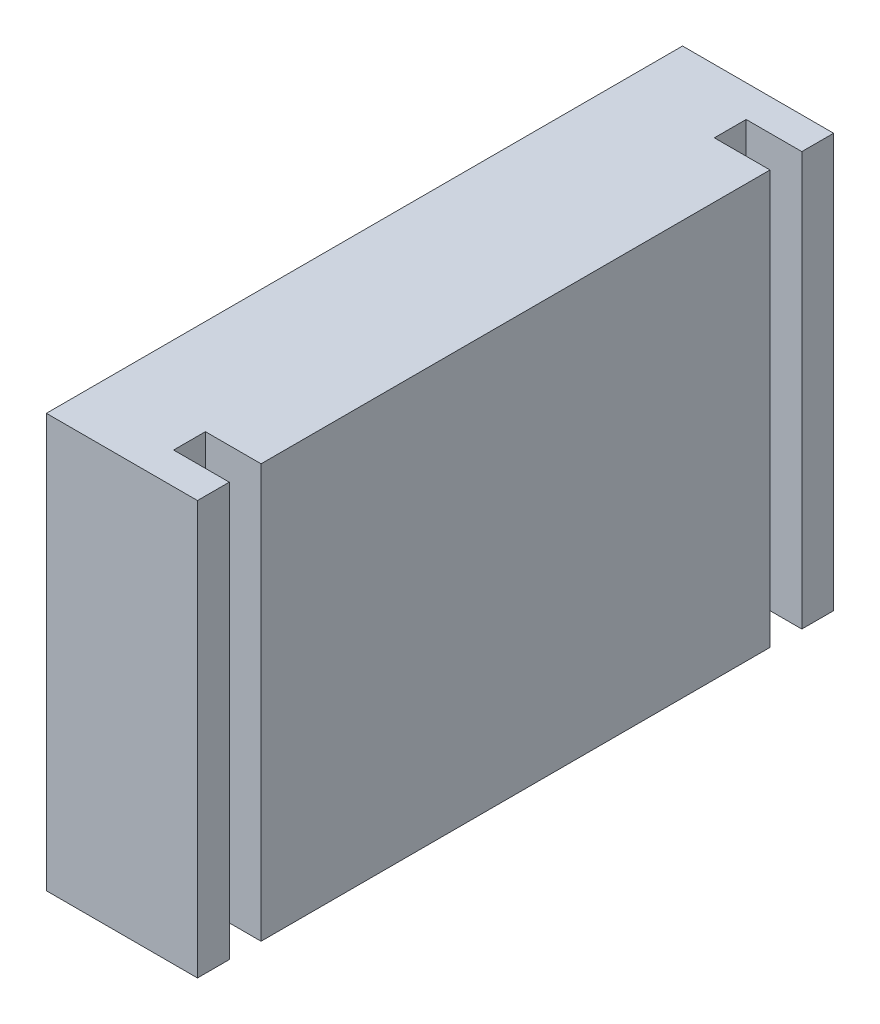
SolidWorks part; units mm, degrees
ref_plane "Alzado" through (0, 0, 0) normal (0, 0, 1) x (1, 0, 0)
ref_plane "Planta" through (0, 0, 0) normal (0, 1, 0) x (1, 0, 0)
ref_plane "Vista lateral" through (0, 0, 0) normal (1, 0, 0) x (0, 0, -1)
sketch "Croquis1" plane through (0, 0, 0) normal (0, 1, 0) x (1, 0, 0)
  line L0 (-12.7137, 38.3585) -> (-10.7137, 38.3585)
  line L1 (-10.7137, 38.3585) -> (-10.7137, 39.3585)
  line L2 (-10.7137, 39.3585) -> (-15.7137, 39.3585)
  line L3 (-15.7137, 39.3585) -> (-15.7137, 19.3585)
  line L4 (-15.7137, 19.3585) -> (-10.7137, 19.3585)
  line L5 (-10.7137, 19.3585) -> (-10.7137, 20.3585)
  line L6 (-10.7137, 20.3585) -> (-12.7137, 20.3585)
  line L7 (-12.7137, 20.3585) -> (-12.7137, 21.3585)
  line L8 (-12.7137, 21.3585) -> (-10.7186, 21.3585)
  line L9 (-12.7137, 38.3585) -> (-12.7137, 37.3585)
  line L10 (-12.7137, 37.3585) -> (-10.7186, 37.3585)
  line L11 (-10.7186, 37.3585) -> (-10.7186, 21.3585)
  dimension "D1" = 20
  dimension "D2" = 1
  dimension "D3" = 1
extrude "Saliente-Extruir3" add sketch "Croquis1" along normal blind 10
sketch "Croquis4" plane through (-10.7137, 0, 0) normal (1, 0, 0) x (0, 0, -1)
  line L0 (39.3585, 0) -> (39.3585, -5)
  line L1 (39.3585, -5) -> (19.3585, -5)
  line L2 (19.3585, 0) -> (19.3585, -5)
  line L3 (39.3585, 0) -> (19.3585, 0)
extrude "Saliente-Extruir4" add sketch "Croquis4" along normal blind 10 separate body
sketch "Croquis5" plane through (0, 0, -19.3585) normal (0, 0, 1) x (1, 0, 0)
  line L1 (-15.7137, 0) -> (-10.7137, 0)
  line L2 (-15.7137, 0) -> (-15.7137, -5)
  line L3 (-15.7137, -5) -> (-10.7137, -5)
  line L4 (-10.7137, 0) -> (-10.7137, -5)
extrude "Saliente-Extruir5" add sketch "Croquis5" against normal blind 20
sketch "Croquis7" plane through (0, 0, 0) normal (0, 1, 0) x (1, 0, 0)
  line L0 (-0.7137, 19.3585) -> (-0.7137, 20.3585)
  line L1 (-0.7137, 39.3585) -> (-0.7137, 19.3585) construction
  line L2 (-0.7137, 20.3585) -> (-12.7137, 20.3585)
  line L3 (-12.7137, 20.3585) -> (-12.7137, 21.3585) construction
  line L4 (-10.7137, 20.3585) -> (-12.7137, 20.3585) construction
  line L5 (-12.7137, 20.3585) -> (-12.7137, 21.3585)
  line L6 (-12.7137, 21.3585) -> (-0.7137, 21.3585)
  line L7 (-0.7137, 21.3585) -> (-0.7137, 20.3585)
  line L8 (-0.7137, 29.3585) -> (-7.5188, 29.3585)
  line L9 (-0.7137, 37.3585) -> (-0.7137, 38.3585)
  line L10 (-12.7137, 37.3585) -> (-0.7137, 37.3585)
  line L11 (-12.7137, 38.3585) -> (-12.7137, 37.3585)
  line L12 (-0.7137, 38.3585) -> (-12.7137, 38.3585)
  line L13 (-0.7137, 39.3585) -> (-0.7137, 38.3585)
  line M1 (-10.7149, 21.3585) -> (-12.7137, 21.3585)
  line M2 (-12.7137, 21.3585) -> (-12.7137, 20.3585)
  line M3 (-12.7137, 20.3585) -> (-10.7137, 20.3585)
  line M6 (-0.7137, 19.3585) -> (-0.7137, 39.3585)
  line M9 (-10.7137, 38.3585) -> (-12.7137, 38.3585)
  line M10 (-12.7137, 38.3585) -> (-12.7137, 37.3585)
  line M11 (-12.7137, 37.3585) -> (-10.7149, 37.3585)
extrude "Cortar-Extruir1" cut sketch "Croquis7" against normal blind 2 contours L12 L10 M6 M9 M10 M11 | L6 L2 M1 M2 M3 M6
sketch "Croquis8" plane through (-0.7137, 0, 0) normal (1, 0, 0) x (0, 0, -1)
  line L1 (19.3585, -5) -> (39.3585, -5)
  line L2 (19.3585, -5) -> (19.3585, 0)
  line L3 (19.3585, 0) -> (39.3585, 0)
  line L4 (39.3585, -5) -> (39.3585, 0)
extrude "Cortar-Extruir2" cut sketch "Croquis8" against normal blind 2
sketch "Croquis9" plane through (0, 10, 0) normal (0, 1, 0) x (1, 0, 0)
  line L1 (-15.7137, 39.3585) -> (-10.7137, 39.3585)
  line L2 (-15.7137, 39.3585) -> (-15.7137, 19.3585)
  line L3 (-15.7137, 19.3585) -> (-10.7137, 19.3585)
  line L4 (-10.7137, 39.3585) -> (-10.7137, 19.3585)
extrude "Cortar-Extruir3" cut sketch "Croquis9" against normal blind 2
sketch "Croquis10" plane through (-2.7137, 0, 0) normal (1, 0, 0) x (0, 0, -1)
  line L1 (39.3585, 0) -> (19.3585, 0)
  line L2 (39.3585, 0) -> (39.3585, -5)
  line L3 (39.3585, -5) -> (19.3585, -5)
  line L4 (19.3585, 0) -> (19.3585, -5)
extrude "Cortar-Extruir5" cut sketch "Croquis10" against normal blind 35
sketch "Croquis11" plane through (0, 0, 0) normal (0, -1, 0) x (1, 0, 0)
  line L0 (-10.7137, -20.3585) -> (-10.7137, -19.3585)
  line L1 (-10.7137, -19.3585) -> (-15.7137, -19.3585)
  line L2 (-15.7137, -19.3585) -> (-15.7137, -39.3585)
  line L3 (-15.7137, -39.3585) -> (-10.7137, -39.3585)
  line L4 (-10.7137, -39.3585) -> (-10.7137, -38.3585)
  line L5 (-10.7137, -38.3585) -> (-12.7137, -38.3585)
  line L6 (-12.7137, -38.3585) -> (-12.7137, -37.3585)
  line L7 (-12.7137, -37.3585) -> (-10.7168, -37.3585)
  line L8 (-10.7168, -37.3585) -> (-12.7137, -37.3585) construction
  line L9 (-10.7168, -37.3585) -> (-10.7177, -21.3585) construction
  line L10 (-10.7168, -37.3585) -> (-10.7177, -21.3585)
  line L11 (-10.7177, -21.3585) -> (-12.7137, -21.3585)
  line L12 (-12.7137, -21.3585) -> (-12.7137, -20.3585)
  line L13 (-12.7137, -20.3585) -> (-10.7137, -20.3585)
extrude "Saliente-Extruir6" add sketch "Croquis11" along normal blind 5
sketch "Croquis12" plane through (-10.7137, 0, 0) normal (1, 0, 0) x (0, 0, -1)
  line L1 (41.0923, -7.1346) -> (14.989, -7.1346)
  line L2 (41.0923, -7.1346) -> (41.0923, 11.3189)
  line L3 (41.0923, 11.3189) -> (14.989, 11.3189)
  line L4 (14.989, -7.1346) -> (14.989, 11.3189)
extrude "Cortar-Extruir6" cut sketch "Croquis12" against normal blind 0.25
